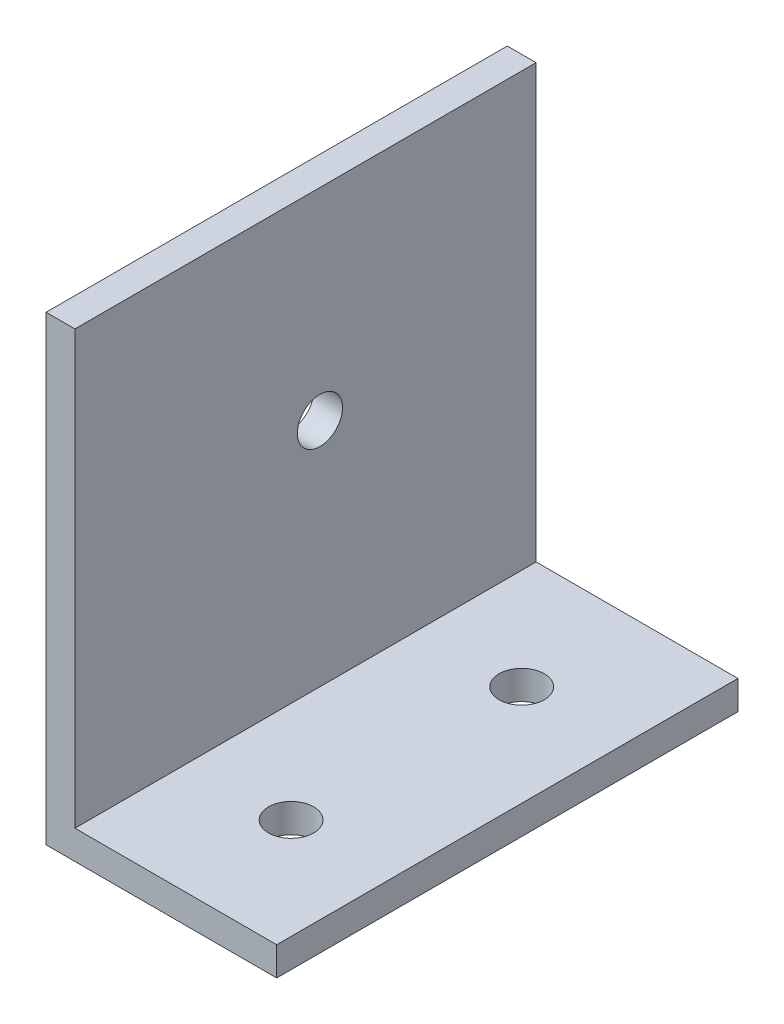
SolidWorks part; units mm, degrees
ref_plane "Front Plane" through (0, 0, 0) normal (0, 0, 1) x (1, 0, 0)
ref_plane "Top Plane" through (0, 0, 0) normal (0, 1, 0) x (1, 0, 0)
ref_plane "Right Plane" through (0, 0, 0) normal (1, 0, 0) x (0, 0, -1)
sketch "Sketch1" plane through (0, 0, 0) normal (0, 0, 1) x (1, 0, 0)
  line L0 (0, 0) -> (0, 50.8)
  line L1 (0, 50.8) -> (3.175, 50.8)
  line L2 (3.175, 50.8) -> (3.175, 3.175)
  line L3 (3.175, 3.175) -> (25.4, 3.175)
  line L4 (25.4, 3.175) -> (25.4, 0)
  line L5 (25.4, 0) -> (0, 0)
  dimension "D1" = 50.8
  dimension "D2" = 25.4
  dimension "D3" = 3.175
  dimension "D4" = 3.175
extrude "Boss-Extrude1" add sketch "Sketch1" along normal blind 50.8
sketch "Sketch2" plane through (0, 0, 0) normal (1, 0, 0) x (0, 0, -1)
  line L0 (0, 3.175) -> (0, 50.8) construction
  line L2 (-50.8, 3.175) -> (0, 3.175) construction
  circle A0 centre (-23.8125, 28.575) radius 2.4892
  dimension "D1" = 4.9784
  dimension "D2" = 23.8125
  dimension "D3" = 25.4
extrude "Cut-Extrude1" cut sketch "Sketch2" along normal through all
sketch "Sketch3" plane through (0, 0, 0) normal (0, 1, 0) x (1, 0, 0)
  line L0 (25.4, -50.8) -> (3.175, -50.8) construction
  circle A0 centre (14.2875, -38.1) radius 2.4892
  circle A1 centre (14.2875, -12.7) radius 2.4892
  point P6 (14.2875, -50.8)
  point P7 (14.2875, -12.7)
  dimension "D1" = 4.9784
  dimension "D2" = 12.7
  dimension "D3" = 25.4
extrude "Cut-Extrude2" cut sketch "Sketch3" along normal through all
